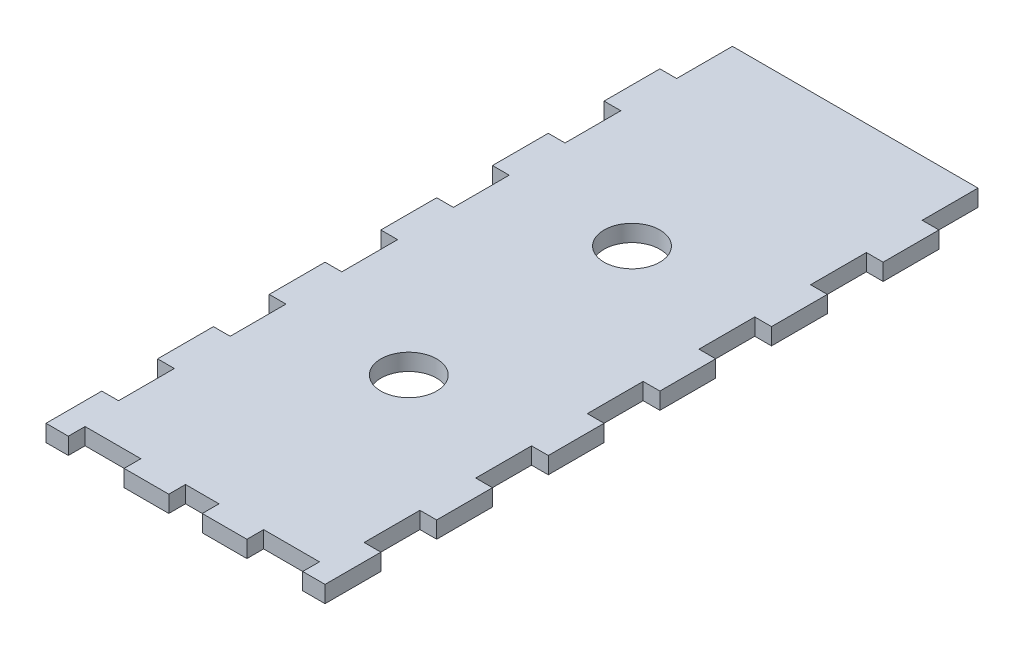
SolidWorks part; units mm, degrees
material "Beech"
ref_plane "Front Plane" through (0, 0, 0) normal (0, 0, 1) x (1, 0, 0)
ref_plane "Top Plane" through (0, 0, 0) normal (0, 1, 0) x (1, 0, 0)
ref_plane "Right Plane" through (0, 0, 0) normal (1, 0, 0) x (0, 0, -1)
sketch "Sketch1" plane through (0, 0, 0) normal (0, 1, 0) x (1, 0, 0)
  line L0 (0, 10) -> (3, 10)
  line L1 (0, 0) -> (50, 0)
  line L2 (0, 0) -> (0, 120)
  line L3 (0, 120) -> (50, 120)
  line L4 (50, 0) -> (50, 120)
  line L5 (3, 10) -> (3, 20)
  line L6 (3, 20) -> (0, 20)
  line L7 (0, 30) -> (3, 30)
  line L8 (3, 30) -> (3, 40)
  line L9 (3, 40) -> (0, 40)
  line L10 (0, 50) -> (3, 50)
  line L11 (3, 50) -> (3, 60)
  line L12 (3, 60) -> (0, 60)
  line L13 (0, 70) -> (3, 70)
  line L14 (3, 70) -> (3, 80)
  line L15 (3, 80) -> (0, 80)
  line L16 (0, 90) -> (3, 90)
  line L17 (3, 90) -> (3, 100)
  line L18 (3, 100) -> (0, 100)
  line L19 (0, 110) -> (3, 110)
  line L20 (3, 110) -> (3, 120)
  line L21 (3, 120) -> (0, 120)
  line L22 (50, 10) -> (47, 10)
  line L23 (47, 10) -> (47, 20)
  line L24 (47, 20) -> (50, 20)
  line L25 (50, 30) -> (47, 30)
  line L26 (47, 30) -> (47, 40)
  line L27 (47, 40) -> (50, 40)
  line L28 (50, 50) -> (47, 50)
  line L29 (47, 50) -> (47, 60)
  line L30 (47, 60) -> (50, 60)
  line L31 (50, 70) -> (47, 70)
  line L32 (47, 70) -> (47, 80)
  line L33 (47, 80) -> (50, 80)
  line L34 (50, 90) -> (47, 90)
  line L35 (47, 90) -> (47, 100)
  line L36 (47, 100) -> (50, 100)
  line L37 (50, 110) -> (47, 110)
  line L38 (47, 110) -> (47, 120)
  line L39 (47, 120) -> (50, 120)
  line L40 (4, 0) -> (4, 3)
  line L41 (4, 3) -> (14, 3)
  line L42 (14, 3) -> (14, 0)
  line L43 (46, 0) -> (46, 3)
  line L44 (46, 3) -> (36, 3)
  line L45 (36, 3) -> (36, 0)
  line L46 (22, 0) -> (22, 3)
  line L47 (22, 3) -> (28, 3)
  line L48 (28, 3) -> (28, 0)
  circle A0 centre (25, 40) radius 5
  circle A1 centre (25, 80) radius 5
  point P9 (25, 0)
  dimension "D3" = 10
  dimension "D4" = 10
  dimension "D1" = 120
  dimension "D2" = 50
  dimension "D5" = 40
  dimension "D6" = 40
  dimension "D7" = 3
  dimension "D8" = 10
  dimension "D9" = 10
  dimension "D11" = 3
  dimension "D13" = 3
  dimension "D14" = 4
  dimension "D15" = 10
  dimension "D16" = 10
  dimension "D17" = 4
  dimension "D18" = 6
  dimension "D19" = 8
  dimension "D10" = 6
  dimension "D12" = 6
extrude "Boss-Extrude1" add sketch "Sketch1" along normal blind 3
